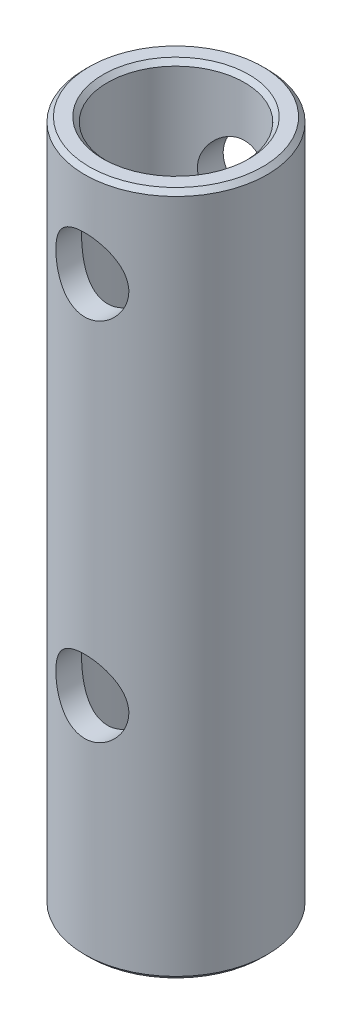
SolidWorks part; units mm, degrees
ref_plane "Front" through (0, 0, 0) normal (0, 0, 1) x (1, 0, 0)
ref_plane "Top" through (0, 0, 0) normal (0, 1, 0) x (1, 0, 0)
ref_plane "Right" through (0, 0, 0) normal (1, 0, 0) x (0, 0, -1)
sketch "Skizze1" plane through (0, 0, 0) normal (0, 1, 0) x (1, 0, 0)
  circle A0 centre (0, 0) radius 4
  circle A1 centre (0, 0) radius 3
  dimension "D1" = 8
  dimension "D2" = 6
extrude "Aufsatz-Linear austragen1" add sketch "Skizze1" along normal blind 30
chamfer "Fase1" distance 0.2 angle 45 4 edges at (0, 0, 4) (0, 30, 4) (0, 0, 3) (0, 30, 3)
sketch "Skizze2" plane through (0, 0, 0) normal (0, 0, 1) x (1, 0, 0)
  line L0 (0, 30) -> (0, 0) construction
  line L1 (3.2, 30) -> (-3.2, 30) construction
  circle A0 centre (0, 26) radius 1.6 construction
  circle A1 centre (0, 26) radius 1.6
  circle A2 centre (0, 10) radius 1.6
  dimension "D1" = 10
extrude "Schnitt-Linear austragen1" cut sketch "Skizze2" against normal mid plane 12
